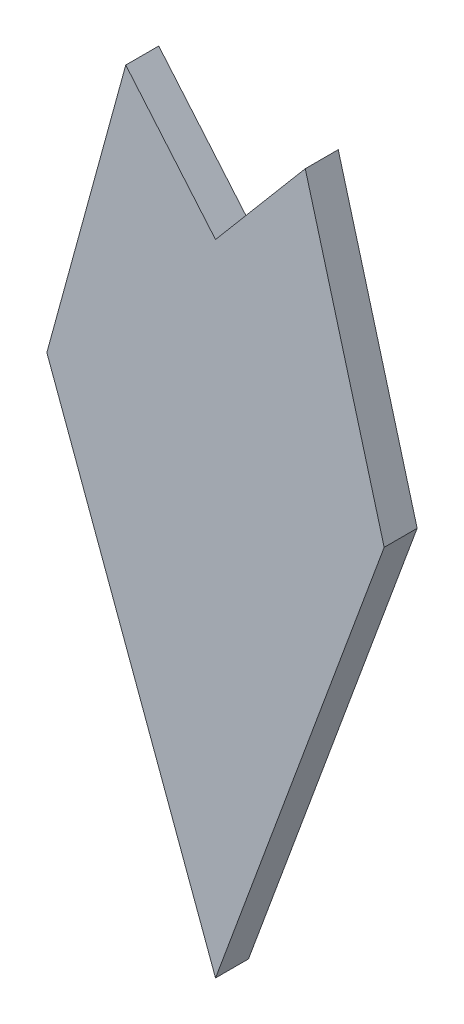
SolidWorks part; units mm, degrees
ref_plane "Plan de face" through (0, 0, 0) normal (0, 0, 1) x (1, 0, 0)
ref_plane "Plan de dessus" through (0, 0, 0) normal (0, 1, 0) x (1, 0, 0)
ref_plane "Plan de droite" through (0, 0, 0) normal (1, 0, 0) x (0, 0, -1)
sketch "Esquisse1" plane through (0, 0, 0) normal (0, 0, 1) x (1, 0, 0)
  line L2 (22.092, 10.6482) -> (24.65, 3.713)
  line L3 (22.092, 10.6482) -> (24.65, 3.713)
  line L9 (24.65, 13.4122) -> (23.2887, 15.0232)
  line L10 (23.2887, 15.0232) -> (22.092, 10.6482)
  line L11 (22.092, 10.6482) -> (24.65, 3.713)
  line L12 (24.65, 3.713) -> (27.208, 10.6482)
  line L13 (27.208, 10.6482) -> (26.0113, 15.0232)
  line L14 (26.0113, 15.0232) -> (24.65, 13.4122)
  line L15 (24.65, 13.4122) -> (23.2887, 15.0232)
  line L16 (23.2887, 15.0232) -> (22.092, 10.6482)
  line L17 (22.092, 10.6482) -> (24.65, 3.713)
  line L18 (24.65, 3.713) -> (27.208, 10.6482)
  line L19 (27.208, 10.6482) -> (26.0113, 15.0232)
  line L20 (26.0113, 15.0232) -> (24.65, 13.4122)
  dimension "D1" = 0
  dimension "D2" = 0
extrude "Boss.-Extru.1" add sketch "Esquisse1" along normal blind 0.5 contours L19 L20 L15 L16 L3 L18
